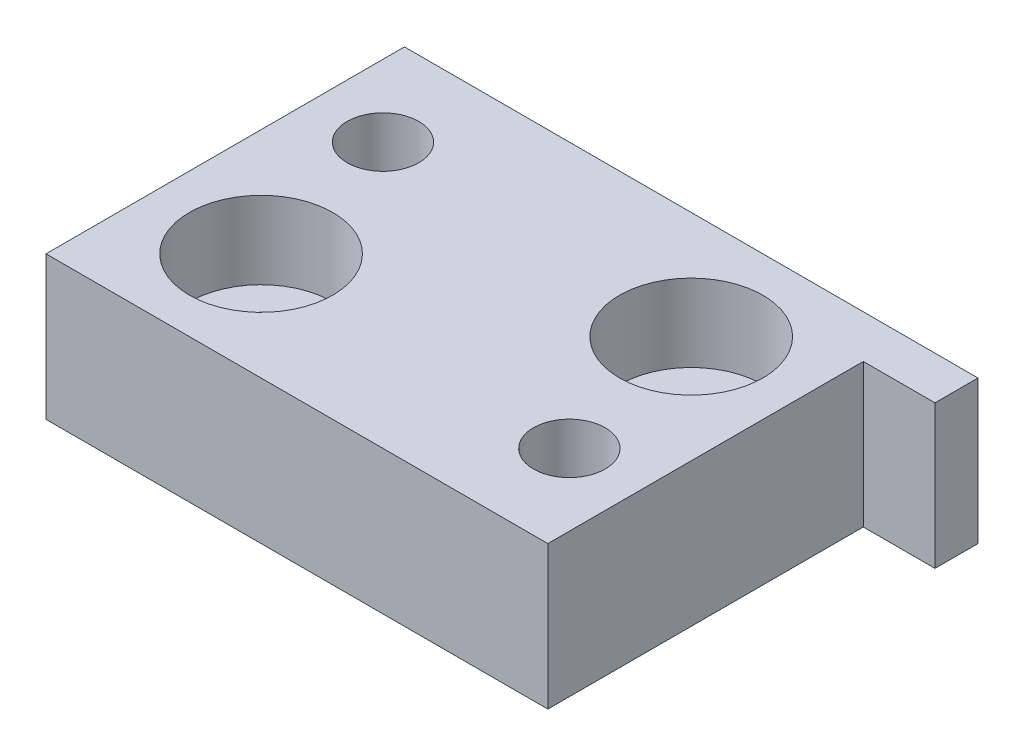
SolidWorks part; units mm, degrees
material "Plain Carbon Steel"
ref_plane "Front Plane" through (0, 0, 0) normal (0, 0, 1) x (1, 0, 0)
ref_plane "Top Plane" through (0, 0, 0) normal (0, 1, 0) x (1, 0, 0)
ref_plane "Right Plane" through (0, 0, 0) normal (1, 0, 0) x (0, 0, -1)
sketch "Sketch1" plane through (0, 0, 0) normal (0, 1, 0) x (1, 0, 0)
  line L1 (-20, -12.5) -> (20, -12.5)
  line L2 (-20, -12.5) -> (-20, 12.5)
  line L3 (-20, 12.5) -> (20, 12.5)
  line L4 (20, -12.5) -> (20, 12.5)
  line L5 (-20, -12.5) -> (20, 12.5) construction
  line L6 (-20, 12.5) -> (20, -12.5) construction
  point P0 (0, 0)
  dimension "D1" = 40
  dimension "D2" = 25
extrude "Boss-Extrude1" add sketch "Sketch1" along normal blind 10
sketch "Sketch3" plane through (0, 10, 0) normal (0, 1, 0) x (1, 0, 0)
  line L0 (20, 12.5) -> (-20, 12.5) construction
  line L1 (20, -12.5) -> (15, -12.5)
  line L2 (20, -12.5) -> (20, 9.5)
  line L3 (20, 9.5) -> (15, 9.5)
  line L4 (15, -12.5) -> (15, 9.5)
  dimension "D1" = 5
  dimension "D2" = 3
extrude "Cut-Extrude2" cut sketch "Sketch3" against normal up to next
hole_wizard "Ø5.0mm Dowel Hole1" positions "Sketch9" profile "Sketch5" hole size "Ø5.0" standard "ISO" end condition through all
sketch "Sketch9" plane through (0, 10, 0) normal (0, 1, 0) x (1, 0, 0)
  line L4 (-2.5, -12.5) -> (-2.5, 12.5) construction
  line L5 (-20, -12.5) -> (15, -12.5) construction
  line L6 (20, 12.5) -> (-20, 12.5) construction
  line L7 (-20, 0) -> (15, 0) construction
  line L8 (-20, 12.5) -> (-20, -12.5) construction
  line L9 (15, 9.5) -> (15, -12.5) construction
  point P31 (10, -6)
  point P33 (-15, 6)
  dimension "D1" = 25
  dimension "D2" = 12
  dimension "D3" = 6
  dimension "D4" = 12.5
sketch "Sketch5" plane through (-15, 10, -6) normal (1, 0, 0) x (0, 0, 1)
  line L0 (0, 0) -> (0, 10)
  line L1 (0, 10) -> (2.5, 10)
  line L2 (2.5, 10) -> (2.5, 0)
  line L5 (2.5, 0) -> (0, 0)
  line L11 (0, -6.35) -> (0, 107.95) construction
  dimension "Thru Hole Dia." = 5
  dimension "Thru Hole Depth" = 10
hole_wizard "CBORE for M5 Hex Socket Head Cap Screw1" positions "Sketch13" profile "Sketch11" counterbore size "M5" standard "ISO" end condition through all
sketch "Sketch13" plane through (0, 10, 0) normal (0, 1, 0) x (1, 0, 0)
  line L0 (-20, 0) -> (15, 0) construction
  line L1 (-20, 12.5) -> (-20, -12.5) construction
  line L2 (15, 9.5) -> (15, -12.5) construction
  line L4 (-2.5, -12.5) -> (-2.5, 12.5) construction
  line L7 (-20, -12.5) -> (15, -12.5) construction
  line L8 (20, 12.5) -> (-20, 12.5) construction
  point P0 (-12.5, -5)
  point P2 (7.5, 5)
  point P27 (0, 0)
  point P30 (0, 0)
  point P37 (-2.5, 0)
  point P38 (-2.5, 0)
  dimension "D1" = 10
  dimension "D2" = 5
  dimension "D3" = 20
  dimension "D4" = 10
sketch "Sketch11" plane through (-12.5, 10, 5) normal (1, 0, 0) x (0, 0, 1)
  line L0 (0, 0) -> (0, 10)
  line L1 (0, 10) -> (2.65, 10)
  line L3 (2.65, 10) -> (2.65, 5.4)
  line L4 (2.65, 5.4) -> (5, 5.4)
  line L5 (5, 5.4) -> (5, 0)
  line L7 (5, 0) -> (0, 0)
  line L11 (0, -6.35) -> (0, 107.95) construction
  dimension "Thru Hole Dia." = 5.3
  dimension "Thru Hole Depth" = 10
  dimension "C'Bore Dia." = 10
  dimension "C'Bore Depth" = 5.4
